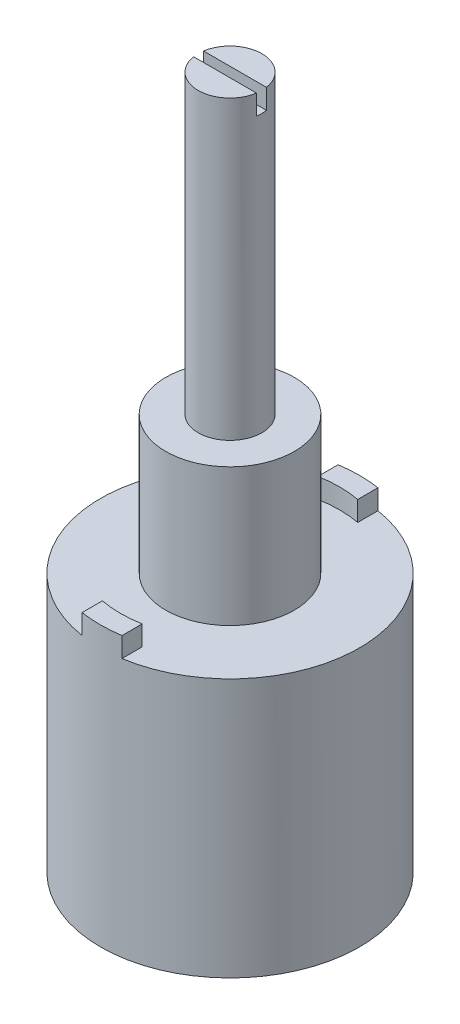
SolidWorks part; units mm, degrees
ref_plane "Front Plane" through (0, 0, 0) normal (0, 0, 1) x (1, 0, 0)
ref_plane "Top Plane" through (0, 0, 0) normal (0, 1, 0) x (1, 0, 0)
ref_plane "Right Plane" through (0, 0, 0) normal (1, 0, 0) x (0, 0, -1)
sketch "Sketch1" plane through (0, 0, 0) normal (0, 1, 0) x (1, 0, 0)
  circle A0 centre (0, 0) radius 6.5
  dimension "D1" = 13
extrude "Boss-Extrude1" add sketch "Sketch1" along normal blind 13
sketch "Sketch2" plane through (0, 13, 0) normal (0, 1, 0) x (1, 0, 0)
  circle A0 centre (0, 0) radius 3.225
  dimension "D1" = 6.45
extrude "Boss-Extrude2" add sketch "Sketch2" along normal blind 6.9
sketch "Sketch3" plane through (0, 19.9, 0) normal (0, 1, 0) x (1, 0, 0)
  circle A0 centre (0, 0) radius 1.6
  dimension "D1" = 3.2
extrude "Boss-Extrude3" add sketch "Sketch3" along normal blind 14.88
sketch "Sketch4" plane through (0, 13, 0) normal (0, 1, 0) x (1, 0, 0)
  line L0 (0, 5.5) -> (0, -5.5)
  line L1 (-1, 5.5) -> (-1, -5.5)
  line L2 (1, 5.5) -> (1, -5.5)
  line L3 (1, -5.5) -> (1, -6.4226)
  line L4 (-1, -5.5) -> (-1, -6.4226)
  line L5 (-1, 5.5) -> (-1, 6.4226)
  line L6 (1, 5.5) -> (1, 6.4226)
  circle A0 centre (0, 0) radius 5.5
  circle A1 centre (0, 0) radius 6.5 construction
  circle M1 centre (0, 0) radius 6.5
  dimension "D1" = 1
  dimension "D2" = 1
  dimension "D3" = 1
extrude "Boss-Extrude4" add sketch "Sketch4" along normal blind 1 contours A0 L2 L6 L5 L1 M1 | A0 L1 L4 L3 L2 M1
sketch "Sketch5" plane through (0, 34.78, 0) normal (0, 1, 0) x (1, 0, 0)
  line L0 (1.6, 0) -> (-1.6, 0)
  line L1 (1.6, 0.25) -> (-1.6, 0.25)
  line L2 (1.6, -0.25) -> (-1.6, -0.25)
  circle A0 centre (0, 0) radius 1.6 construction
  circle A3 centre (0, 0) radius 1.6
  circle A4 centre (0, 0) radius 1.6
  circle A5 centre (0, 0) radius 1.6
  circle A6 centre (0, 0) radius 1.6
  circle M1 centre (0, 0) radius 1.6
  dimension "D1" = 0.25
  dimension "D2" = 0.25
  dimension "D3" = 0
  dimension "D4" = 0
extrude "Cut-Extrude1" cut sketch "Sketch5" against normal blind 1 contours L1 L0 M1 | L2 L0 M1
